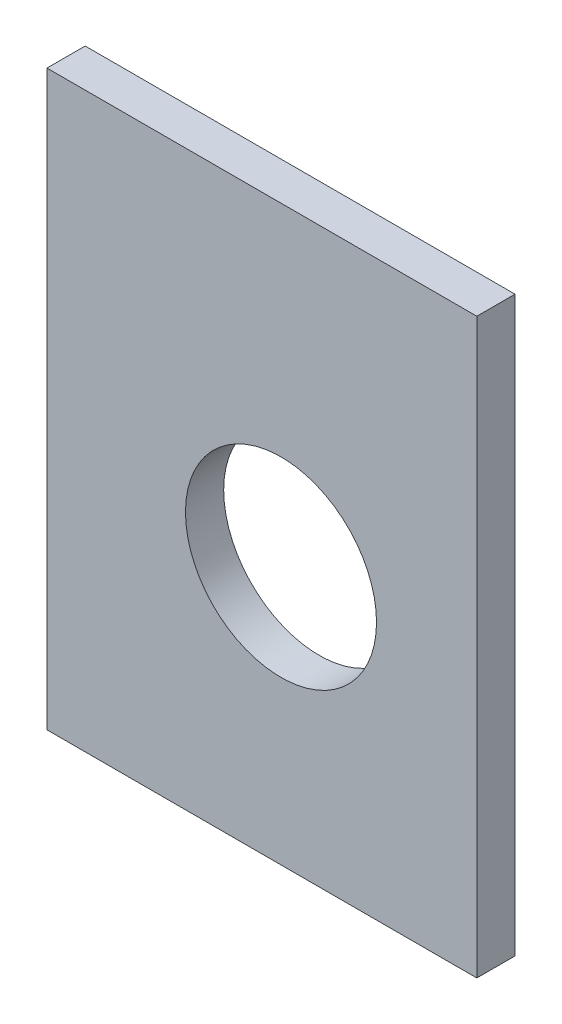
SolidWorks part; units mm, degrees
ref_plane "Front Plane" through (0, 0, 0) normal (0, 0, 1) x (1, 0, 0)
ref_plane "Top Plane" through (0, 0, 0) normal (0, 1, 0) x (1, 0, 0)
ref_plane "Right Plane" through (0, 0, 0) normal (1, 0, 0) x (0, 0, -1)
sketch "Sketch1" plane through (0, 0, 0) normal (0, 0, 1) x (1, 0, 0)
  line L5 (-22.5, -30) -> (22.5, -30)
  line L6 (-22.5, -30) -> (-22.5, 30)
  line L7 (-22.5, 30) -> (22.5, 30)
  line L8 (22.5, -30) -> (22.5, 30)
  line L9 (-22.5, -30) -> (22.5, 30) construction
  line L10 (-22.5, 30) -> (22.5, -30) construction
  circle A2 centre (2, -3) radius 10
  point P0 (0, 0)
  dimension "D3" = 20
  dimension "D1" = 60
  dimension "D2" = 45
  dimension "D4" = 20.5
  dimension "D5" = 3
extrude "Boss-Extrude1" add sketch "Sketch1" along normal blind 4
